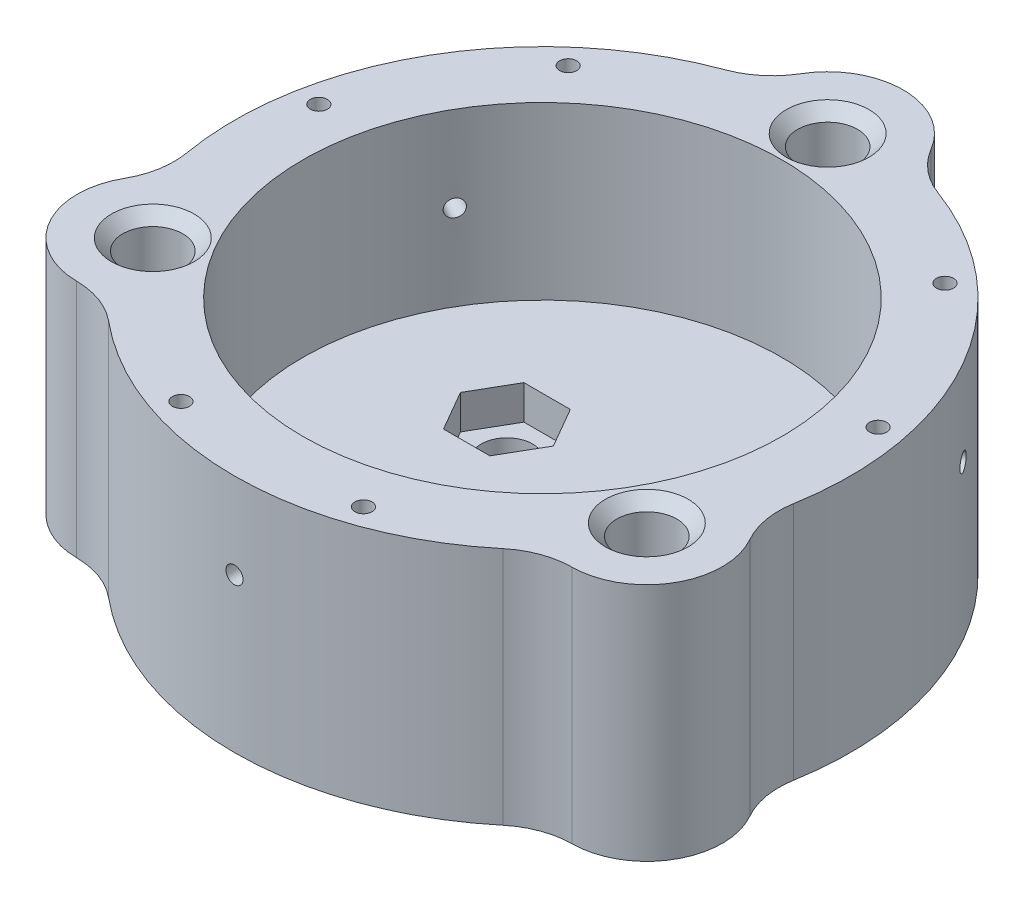
SolidWorks part; units mm, degrees
ref_plane "Спереди" through (0, 0, 0) normal (0, 0, 1) x (1, 0, 0)
ref_plane "Сверху" through (0, 0, 0) normal (0, 1, 0) x (1, 0, 0)
ref_plane "Справа" through (0, 0, 0) normal (1, 0, 0) x (0, 0, -1)
sketch "Эскиз1" plane through (0, 0, 0) normal (0, 1, 0) x (1, 0, 0)
  circle A0 centre (0, 0) radius 25 construction
  circle A1 centre (0, 25) radius 2.625
  circle A3 centre (0, 25) radius 6.625
  circle A4 centre (0, 0) radius 21
  circle A5 centre (0, 0) radius 27
  circle A6 centre (21.6506, -12.5) radius 6.625
  circle A7 centre (21.6506, -12.5) radius 2.625
  circle A8 centre (-21.6506, -12.5) radius 6.625
  circle A9 centre (-21.6506, -12.5) radius 2.625
  dimension "D1" = 50
  dimension "D2" = 5.25
  dimension "D3" = 4
  dimension "D5" = 4
  dimension "D4" = 2
  dimension "D6" = 3
extrude "Бобышка-Вытянуть1" add sketch "Эскиз1" along normal blind 15 contours A5 A3 A1 | A3 A5 A1 A4 | A6 A5 A3 A4 | A8 A4 A3 A5 | A7 A5 A6 A4 | A7 A5 A6 | A8 A5 A6 A4 | A9 A5 A8 | A9 A5 A8 A4
sketch "Эскиз2" plane through (0, 0, 0) normal (0, -1, 0) x (1, 0, 0)
  arc A27 (25.9493, 7.4589) -> (19.4343, 18.7433) centre (21.6506, 12.5) ccw
  arc A28 (6.515, -26.2022) -> (25.9493, 7.4589) centre (0, 0) ccw
  arc A29 (-6.515, -26.2022) -> (6.515, -26.2022) centre (0, -25) ccw
  arc A30 (-25.9493, 7.4589) -> (-6.515, -26.2022) centre (0, 0) ccw
  arc A31 (-19.4343, 18.7433) -> (-25.9493, 7.4589) centre (-21.6506, 12.5) ccw
  arc A32 (19.4343, 18.7433) -> (-19.4343, 18.7433) centre (0, 0) ccw
  arc A33 (25.9493, 7.4589) -> (19.4343, 18.7433) centre (21.6506, 12.5) ccw
  arc A34 (6.515, -26.2022) -> (25.9493, 7.4589) centre (0, 0) ccw
  arc A35 (-6.515, -26.2022) -> (6.515, -26.2022) centre (0, -25) ccw
  arc A36 (-25.9493, 7.4589) -> (-6.515, -26.2022) centre (0, 0) ccw
  arc A37 (-19.4343, 18.7433) -> (-25.9493, 7.4589) centre (-21.6506, 12.5) ccw
  arc A38 (19.4343, 18.7433) -> (-19.4343, 18.7433) centre (0, 0) ccw
  dimension "D1" = 0
extrude "Бобышка-Вытянуть2" add sketch "Эскиз2" along normal blind 6
fillet "Скругление1" radius 7 6 edges at (6.515, 4.5, -26.2022) (-6.515, 4.5, -26.2022) (-25.9493, 4.5, 7.4589) (-19.4343, 4.5, 18.7433) (19.4343, 4.5, 18.7433) (25.9493, 4.5, 7.4589)
chamfer "Фаска1" distance 1 angle 45 3 edges at (0, 15, -22.375) (21.6506, 15, 15.125) (-21.6506, 15, 15.125)
sketch "Эскиз4" plane through (0, -6, 0) normal (0, -1, 0) x (1, 0, 0)
  circle A0 centre (0, 0) radius 8.5 construction
  circle A1 centre (0, 8.5) radius 2.25
  circle A2 centre (7.3612, -4.25) radius 2.25
  circle A3 centre (-7.3612, -4.25) radius 2.25
  dimension "D1" = 17
  dimension "D2" = 4.5
  dimension "D3" = 3
extrude "Вырез-Вытянуть1" cut sketch "Эскиз4" against normal through all
sketch "Эскиз5" plane through (0, 0, 0) normal (0, 1, 0) x (1, 0, 0)
  line L0 (2.0352, -12.025) -> (4.0703, -8.5)
  line L1 (5.3261, 0.725) -> (9.3964, 0.725)
  line L2 (9.3964, 0.725) -> (11.4315, 4.25)
  line L3 (11.4315, 4.25) -> (9.3964, 7.775)
  line L4 (9.3964, 7.775) -> (5.3261, 7.775)
  line L5 (5.3261, 7.775) -> (3.2909, 4.25)
  line L6 (3.2909, 4.25) -> (5.3261, 0.725)
  line L7 (4.0703, -8.5) -> (2.0352, -4.975)
  line L8 (2.0352, -4.975) -> (-2.0352, -4.975)
  line L9 (-2.0352, -4.975) -> (-4.0703, -8.5)
  line L10 (-4.0703, -8.5) -> (-2.0352, -12.025)
  line L11 (-2.0352, -12.025) -> (2.0352, -12.025)
  line L12 (-11.4315, 4.25) -> (-9.3964, 0.725)
  line L13 (-9.3964, 0.725) -> (-5.3261, 0.725)
  line L14 (-5.3261, 0.725) -> (-3.2909, 4.25)
  line L15 (-3.2909, 4.25) -> (-5.3261, 7.775)
  line L16 (-5.3261, 7.775) -> (-9.3964, 7.775)
  line L17 (-9.3964, 7.775) -> (-11.4315, 4.25)
  circle A2 centre (7.3612, 4.25) radius 3.525 construction
  circle A3 centre (0, -8.5) radius 3.525 construction
  circle A4 centre (-7.3612, 4.25) radius 3.525 construction
  circle A5 centre (0, -8.5) radius 2.25 construction
  dimension "D1" = 7.05
  dimension "D2" = 3
extrude "Вырез-Вытянуть2" cut sketch "Эскиз5" against normal blind 3
sketch "Эскиз6" plane through (0, 15, 0) normal (0, 1, 0) x (1, 0, 0)
  line L0 (0, 0) -> (0, -25) construction
  line L1 (-8, -23.6854) -> (8, -23.6854) construction
  circle A0 centre (0, 0) radius 25 construction
  circle A1 centre (-8, -23.6854) radius 0.75
  circle A2 centre (8, -23.6854) radius 0.75
  circle A3 centre (-16.5122, 18.7709) radius 0.75
  circle A4 centre (-24.5122, 4.9145) radius 0.75
  circle A5 centre (24.5122, 4.9145) radius 0.75
  circle A6 centre (16.5122, 18.7709) radius 0.75
  dimension "D2" = 1.5
  dimension "D3" = 1.5
  dimension "D1" = 16
  dimension "D4" = 3
extrude "Вырез-Вытянуть3" cut sketch "Эскиз6" against normal through all
sketch "Эскиз7" plane through (0, 0, 0) normal (0, 0, 1) x (1, 0, 0)
  line L0 (17.2802, 15) -> (-17.2802, 15) construction
  line L1 (0, 15) -> (0, 0) construction
  circle A0 centre (0, 7.5) radius 0.75
  dimension "D1" = 1.5
extrude "Вырез-Вытянуть4" cut sketch "Эскиз7" along normal through all
pattern_circular "Круговой массив1" count 3 over 360 about axis through (0, 15, 0) along (0, -1, 0) of "Вырез-Вытянуть4"
equation "\"motor_diameter\"= 30"
equation "\"mm_diameter\"= IIF ( \"motor_diameter\" < 34 , 41 , \"motor_diameter\" + 8 )"
equation "\"upper_shafts_diameter\"= 5"
equation "\"upper_shats_length\"= 180"
equation "\"upper_bearing_d1\"= 10"
equation "\"upper_bearing_d2\"= 5"
equation "\"upper_bearing_h\"= 15"
equation "\"lower_shafts_diameter\"= 5"
equation "\"lower_shafts_length\"= 180"
equation "\"lower_bearing_d1\"= 10"
equation "\"lower_bearing_d2\"= 5"
equation "\"lower_bearing_h\"= 15"
equation "\"print_offset\"= 0.5"
equation "\"bh_screws_d\"= 2"
equation "\"bh_screws_h\"= 20"
equation "\"bh_screws_hh_d\"= 3.4"
equation "\"bh_screws_hh_h\"= 2"
equation "\"bh_nut_d\"= 3.8"
equation "\"bh_nut_h\"= 2"
equation "\"motor_screws_d\"= 3"
equation "\"motor_screws_h\"= 16"
equation "\"motor_screws_hh_d\"= 5.5"
equation "\"motor_screws_hh_h\"= 3"
equation "\"plate_hole_distance\"= 25.4"
equation "\"plate_screws_d\"= 6.5"
equation "\"shafts_diameter\"= IIF ( \"mm_diameter\" < 42 , 42 + 8 , \"mm_diameter\" + 8 )"
equation "\"central_hole_diameter\"= 8"
equation "\"bh_thikness\"= 4"
equation "\"D1@Эскиз1\"=\"shafts_diameter\""
equation "\"D2@Эскиз1\" = \"upper_shafts_diameter\" + \"print_offset\" / 2"
equation "\"D3@Эскиз1\"=\"bh_thikness\""
equation "\"D1@Бобышка-Вытянуть1\"= \"upper_bearing_h\""
equation "\"D1@Бобышка-Вытянуть2\"=6"
equation "\"D4@Эскиз1\"=\"D3@Эскиз1\"/2"
equation "\"D2@Эскиз4\"=\"ends_screws_d\"+\"print_offset\""
equation "\"D1@Эскиз5\"=\"ends_nut_d\"+\"print_offset\"/2"
equation "\"D1@Вырез-Вытянуть2\"=\"ends_nut_h\""
equation "\"D5@Эскиз1\"=\"bh_thikness\""
equation "\"ends_screws_d\"= 4"
equation "\"ends_screws_h\"= 16"
equation "\"ends_screws_hh_d\"= 6.7"
equation "\"ends_screws_hh_h\"= 4.1"
equation "\"ends_nut_d\"= 6.8"
equation "\"ends_nut_h\"= 3"
equation "\"D2@Эскиз6\"=\"bh_screws_d\"-\"print_offset\""
equation "\"D3@Эскиз6\"=\"D2@Эскиз6\""
equation "\"D1@Эскиз7\"=\"bh_screws_d\"-\"print_offset\""
